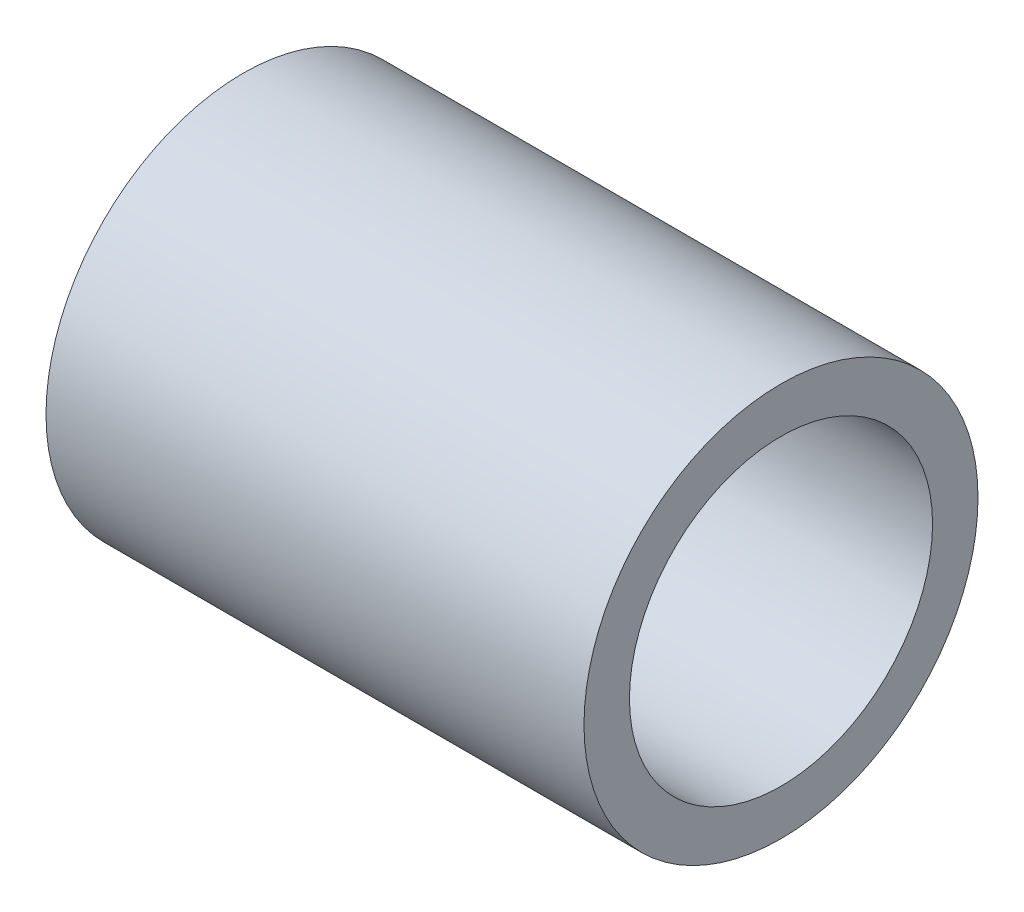
SolidWorks part; units mm, degrees
material "Nylon 101"
ref_plane "Спереди" through (0, 0, 0) normal (0, 0, 1) x (1, 0, 0)
ref_plane "Сверху" through (0, 0, 0) normal (0, 1, 0) x (1, 0, 0)
ref_plane "Справа" through (0, 0, 0) normal (1, 0, 0) x (0, 0, -1)
sketch "Эскиз1" plane through (0, 0, 0) normal (0, 0, 1) x (1, 0, 0)
  line L0 (0, 0) -> (91, 0) construction
  line L6 (-17.75, 13) -> (17.75, 13)
  line L19 (-17.75, 13) -> (-17.75, 10)
  line L20 (-17.75, 10) -> (17.75, 10)
  line L21 (17.75, 10) -> (17.75, 13)
  line L22 (0, 0) -> (0, 50000) construction
  point P9 (-75, 47.5)
  point P10 (75, 47.5)
  dimension "D2" = 20
  dimension "D3" = 35.5
  dimension "D10" = 26
revolve "Повернуть1" add sketch "Эскиз1" angle 360 about L0
